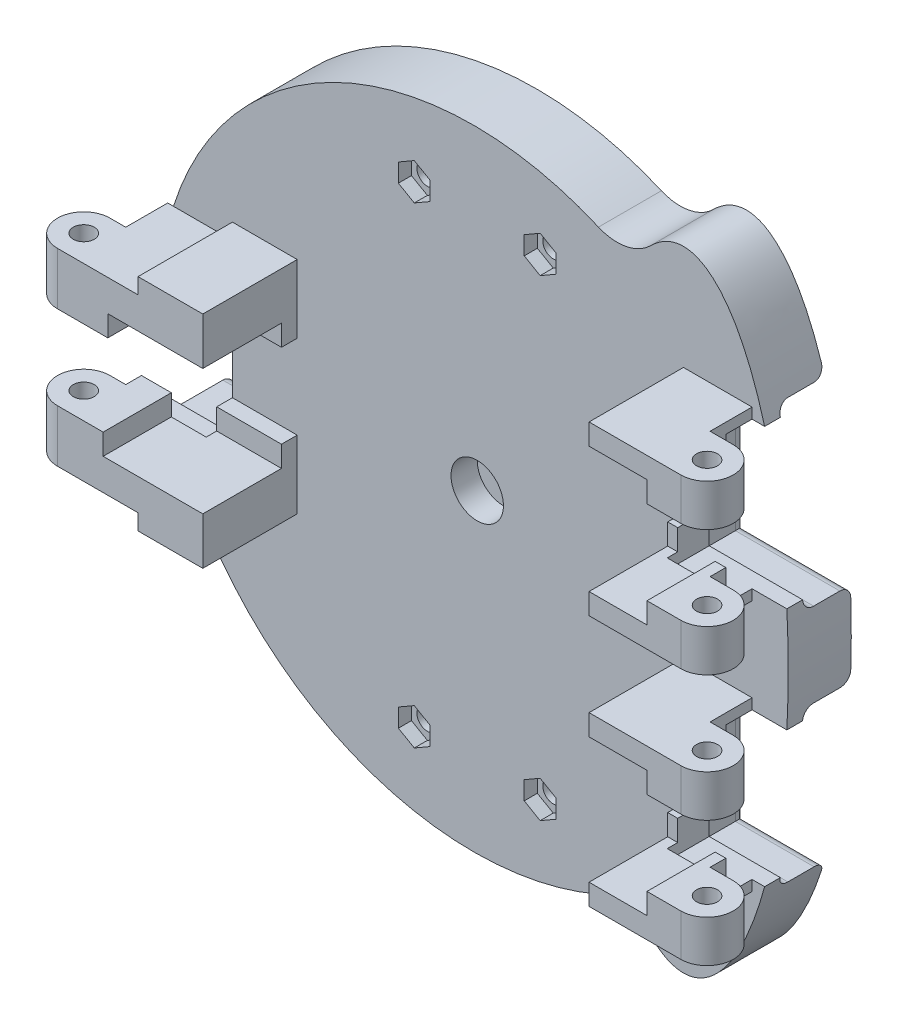
SolidWorks part; units mm, degrees
ref_plane "Front Plane" through (0, 0, 0) normal (1, 0, 0) x (0, 1, 0)
ref_plane "Top Plane" through (0, 0, 0) normal (0, 0, 1) x (0, 1, 0)
ref_plane "Right Plane" through (0, 0, 0) normal (0, 1, 0) x (-1, 0, 0)
sketch "Sketch1" plane through (0, 0, 0) normal (0, 0, 1) x (0, 1, 0)
  line L0 (0, 0) -> (0, 80) construction
  line L1 (0, 0) -> (0, -20) construction
  line L2 (-60, 40) -> (-60, -25.0104) construction
  arc A0 (55.0788, 16.2024) -> (-55.0788, 16.2024) centre (0, 40) ccw
  arc A1 (-56.9566, 6.2888) -> (-55.0788, 16.2024) centre (-63.3406, 12.6327) ccw
  arc A2 (55.0788, 16.2024) -> (56.9566, 6.2888) centre (63.3406, 12.6327) ccw
  ellipse E0 centre (0, 0) end of major axis (60, 0) minor radius 20 (-56.9566, 6.2888) -> (56.9566, 6.2888) ccw
  dimension "D3" = 120
  dimension "D2" = 18
  dimension "D4" = 18
  dimension "D1" = 80
extrude "Boss-Extrude1" add sketch "Sketch1" along normal blind 12
sketch "Sketch3" plane through (0, 0, 12) normal (0, 0, 1) x (1, 0, 0)
  line L0 (20, 0) -> (-100, 0) construction
  arc A0 (-16.2024, 55.0788) -> (-16.2024, -55.0788) centre (-40, 0) ccw construction
  circle A1 centre (-39.3259, 0) radius 5
  ellipse E0 centre (0, 0) end of major axis (0, 60) minor radius 20 (-6.2888, -56.9566) -> (-6.2888, 56.9566) ccw construction
  dimension "D1" = 10
extrude "Cut-Extrude1" cut sketch "Sketch3" against normal blind 5
sketch "Sketch4" plane through (0, 0, 12) normal (0, 0, 1) x (1, 0, 0)
  line L0 (-39.3259, 0) -> (-39.3259, -45) construction
  line L1 (-39.3259, 0) -> (-39.3259, 45) construction
  line L2 (-51.3259, -45) -> (-39.3259, -45) construction
  line L3 (-39.3259, -45) -> (-27.3259, -45) construction
  line L4 (-39.3259, 45) -> (-27.3259, 45) construction
  line L5 (-39.3259, 45) -> (-51.3259, 45) construction
  line L7 (-51.3259, 41.5) -> (-48.2948, 43.25)
  line L8 (-48.2948, 43.25) -> (-48.2948, 46.75)
  line L9 (-48.2948, 46.75) -> (-51.3259, 48.5)
  line L10 (-51.3259, 48.5) -> (-54.357, 46.75)
  line L11 (-54.357, 46.75) -> (-54.357, 43.25)
  line L12 (-54.357, 43.25) -> (-51.3259, 41.5)
  line L13 (-27.3259, 41.5) -> (-24.2948, 43.25)
  line L14 (-24.2948, 43.25) -> (-24.2948, 46.75)
  line L15 (-24.2948, 46.75) -> (-27.3259, 48.5)
  line L16 (-27.3259, 48.5) -> (-30.357, 46.75)
  line L17 (-30.357, 46.75) -> (-30.357, 43.25)
  line L18 (-30.357, 43.25) -> (-27.3259, 41.5)
  line L19 (-51.3259, -48.5) -> (-48.2948, -46.75)
  line L20 (-48.2948, -46.75) -> (-48.2948, -43.25)
  line L21 (-48.2948, -43.25) -> (-51.3259, -41.5)
  line L22 (-51.3259, -41.5) -> (-54.357, -43.25)
  line L23 (-54.357, -43.25) -> (-54.357, -46.75)
  line L24 (-54.357, -46.75) -> (-51.3259, -48.5)
  line L25 (-27.3259, -48.5) -> (-24.2948, -46.75)
  line L26 (-24.2948, -46.75) -> (-24.2948, -43.25)
  line L27 (-24.2948, -43.25) -> (-27.3259, -41.5)
  line L28 (-27.3259, -41.5) -> (-30.357, -43.25)
  line L29 (-30.357, -43.25) -> (-30.357, -46.75)
  line L30 (-30.357, -46.75) -> (-27.3259, -48.5)
  circle A2 centre (-51.3259, 45) radius 3.0311 construction
  circle A3 centre (-27.3259, 45) radius 3.0311 construction
  circle A4 centre (-51.3259, -45) radius 3.0311 construction
  circle A5 centre (-27.3259, -45) radius 3.0311 construction
  dimension "D1" = 45
  dimension "D2" = 45
  dimension "D3" = 12
  dimension "D4" = 12
  dimension "D5" = 12
  dimension "D6" = 12
  dimension "D7" = 7
  dimension "D8" = 7
  dimension "D9" = 7
  dimension "D10" = 7
extrude "Cut-Extrude2" cut sketch "Sketch4" against normal blind 2.5
sketch "Sketch5" plane through (0, 0, 12) normal (0, 0, 1) x (1, 0, 0)
  line L0 (-39.3259, 0) -> (20, 0) construction
  line L1 (-39.3259, 0) -> (-100, 0) construction
  line L2 (-100, 0) -> (-100, 8) construction
  line L3 (-100, 0) -> (-100, -8) construction
  line L4 (-100, 8) -> (-86, 8)
  line L8 (-100, -8) -> (-86, -8)
  line L14 (-105, -8) -> (-100, -8)
  line L15 (-100, 8) -> (-105, 8)
  line L19 (-73.6498, 16) -> (-73.6498, 8)
  line L20 (-73.6498, 8) -> (-86, 8)
  line L21 (-86, -8) -> (-73.6498, -8)
  line L22 (-73.6498, -8) -> (-73.6498, -16)
  line L25 (-86, 17.9882) -> (-86, 21)
  line L27 (-86, 21) -> (-73.6498, 21)
  line L28 (-73.6498, 21) -> (-73.6498, 16)
  line L29 (-86, -17.9929) -> (-86, -21)
  line L30 (-86, -21) -> (-73.6498, -21)
  line L31 (-73.6498, -21) -> (-73.6498, -16)
  line L36 (-86, -17.9929) -> (-117, -17.9929)
  line L37 (-86, 17.9882) -> (-117, 17.9882)
  line L38 (-117, 17.9882) -> (-117, 8)
  line L39 (-117, 8) -> (-105, 8)
  line L40 (-117, -17.9929) -> (-117, -8)
  line L41 (-117, -8) -> (-105, -8)
  arc A0 (-16.2024, 55.0788) -> (-16.2024, -55.0788) centre (-40, 0) ccw construction
  ellipse E0 centre (0, 0) end of major axis (0, 60) minor radius 20 (-6.2888, -56.9566) -> (-6.2888, 56.9566) ccw construction
  dimension "D1" = 8
  dimension "D2" = 8
  dimension "D3" = 31
extrude "Boss-Extrude2" add sketch "Sketch5" along normal blind 18
sketch "Sketch6" plane through (0, 0, 12) normal (0, 0, 1) x (1, 0, 0)
  line L0 (0, 0) -> (-39.3259, 0) construction
  line L1 (0, 0) -> (20, 0) construction
  line L2 (20, 0) -> (20, 8) construction
  line L3 (20, 0) -> (20, -8) construction
  line L4 (20, 8) -> (-39.3259, 8) construction
  line L5 (-39.3259, 8) -> (-39.3259, 0) construction
  line L6 (-39.3259, 0) -> (-39.3259, -8) construction
  line L7 (-39.3259, -8) -> (20, -8) construction
  line L8 (20, 8) -> (20, 16) construction
  line L9 (20, 16) -> (20, 32) construction
  line L10 (20, 32) -> (20, 40) construction
  line L11 (20, -8) -> (20, -16) construction
  line L12 (20, -16) -> (20, -32) construction
  line L13 (20, -32) -> (20, -40) construction
  line L15 (20, 40) -> (0, 40)
  line L16 (0, 40) -> (0, 32)
  line L17 (0, 32) -> (20, 32)
  line L18 (20, 8) -> (0, 8)
  line L19 (0, 8) -> (0, 16)
  line L20 (0, 16) -> (20, 16)
  line L23 (20, -16) -> (0, -16)
  line L24 (0, -16) -> (0, -8)
  line L25 (0, -8) -> (20, -8)
  line L27 (20, -40) -> (0, -40)
  line L28 (0, -40) -> (0, -32)
  line L29 (0, -32) -> (18.7036, -32)
  line L30 (20, 40) -> (30, 40)
  line L31 (30, 40) -> (30, 32)
  line L32 (30, 32) -> (20, 32)
  line L33 (20, 16) -> (30, 16)
  line L34 (30, 16) -> (30, 8)
  line L35 (30, 8) -> (20, 8)
  line L36 (20, -8) -> (30, -8)
  line L37 (30, -8) -> (30, -16)
  line L38 (30, -16) -> (20, -16)
  line L42 (18.7036, -32) -> (30, -32)
  line L43 (30, -32) -> (30, -40)
  line L44 (30, -40) -> (20, -40)
  ellipse E0 centre (0, 0) end of major axis (0, 60) minor radius 20 (-6.2888, -56.9566) -> (-6.2888, 56.9566) ccw construction
  dimension "D1" = 8
  dimension "D2" = 8
  dimension "D3" = 8
  dimension "D4" = 16
  dimension "D5" = 8
  dimension "D6" = 8
  dimension "D7" = 16
  dimension "D8" = 8
  dimension "D9" = 10
extrude "Boss-Extrude3" add sketch "Sketch6" along normal blind 18
sketch "Sketch11" plane through (0, 0, 12) normal (0, 0, 1) x (1, 0, 0)
  line L0 (-51.3259, 48.5) -> (-51.3259, 41.5) construction
  line L1 (-51.3259, 41.5) -> (-51.3259, -41.5) construction
  line L2 (-51.3259, -41.5) -> (-51.3259, -48.5) construction
  line L3 (-51.3259, -48.5) -> (-27.3259, -48.5) construction
  line L4 (-27.3259, -48.5) -> (-27.3259, -41.5) construction
  line L5 (-27.3259, -41.5) -> (-27.3259, 41.5) construction
  line L6 (-27.3259, 41.5) -> (-27.3259, 48.5) construction
  line L7 (-27.3259, 48.5) -> (-51.3259, 48.5) construction
  circle A0 centre (-51.3259, 45) radius 2
  circle A1 centre (-51.3259, -45) radius 2
  circle A2 centre (-27.3259, -45) radius 2
  circle A3 centre (-27.3259, 45) radius 2
  dimension "D1" = 4
  dimension "D2" = 4
  dimension "D3" = 4
  dimension "D4" = 4
extrude "Cut-Extrude5" cut sketch "Sketch11" against normal blind 20
sketch "Sketch14" plane through (0, 0, 0) normal (0, 0, -1) x (1, 0, 0)
  line L0 (-100, 0) -> (-86, 0) construction
  line L1 (20, 0) -> (0, 0) construction
  line L2 (-86, 0) -> (-86, 14)
  line L3 (-86, 0) -> (-86, -14)
  line L6 (-86, 14) -> (-86, 16)
  line L7 (-97.8273, 16) -> (-86, 16)
  line L8 (-97.8273, -16) -> (-86, -16)
  line L9 (-86, -16) -> (-86, -14)
  arc A0 (-16.2024, 55.0788) -> (-16.2024, -55.0788) centre (-40, 0) ccw construction
  arc A2 (-97.8273, 16) -> (-97.8273, -16) centre (-40, 0) ccw
  ellipse E0 centre (0, 0) end of major axis (0, -60) minor radius 20 (-6.2888, -56.9566) -> (-6.2888, 56.9566) ccw construction
  dimension "D1" = 14
  dimension "D2" = 14
  dimension "D3" = 14
extrude "Cut-Extrude13" cut sketch "Sketch14" against normal blind 12
sketch "Sketch16" plane through (0, -40, 0) normal (0, -1, 0) x (1, 0, 0)
  line L2 (17.5, 25) -> (17.5, 12) construction
  line L3 (14.9071, 12) -> (30, 12) construction
  circle A0 centre (17.5, 25) radius 2
  dimension "D2" = 4
  dimension "D1" = 13
extrude "Cut-Extrude14" cut sketch "Sketch16" against normal blind 90
sketch "Sketch17" plane through (0, -40, 0) normal (0, -1, 0) x (1, 0, 0)
  line L0 (17.5, 30) -> (30, 30)
  line L1 (30, 30) -> (30, 20)
  line L2 (30, 30) -> (30, 12) construction
  line L3 (30, 20) -> (17.5, 20)
  arc A0 (17.5, 20) -> (17.5, 30) centre (17.5, 25) ccw
extrude "Cut-Extrude15" cut sketch "Sketch17" against normal blind 81
sketch "Sketch20" plane through (0, 0, 0) normal (0, 0, -1) x (1, 0, 0)
  line L0 (22.5, 32) -> (-0.0929, 32) construction
  line L1 (-0.0929, 32) -> (-0.0929, -33.9584) construction
  line L2 (16.9181, -32) -> (-0.0929, -32) construction
  line L3 (22.5, -16) -> (-0.0929, -16) construction
  line L4 (23.5, 16) -> (-0.0929, 16) construction
  line L5 (22.5, 16) -> (17.5, 16) construction
  line L6 (23.5, 40) -> (-0.0929, 40) construction
  line L7 (22.5, 40) -> (17.5, 40) construction
  line L8 (-0.0929, 40) -> (-0.0929, 32) construction
  line L9 (22.5, -40) -> (-0.0929, -40) construction
  line L10 (-0.0929, -40) -> (-0.0929, -33.9584) construction
  line L11 (14.9071, 40) -> (-0.0929, 40)
  line L13 (19.8214, 8) -> (-0.0929, 8)
  line L14 (-0.0929, 8) -> (-0.0929, 40)
  line L17 (14.9071, -40) -> (-0.0929, -40)
  line L18 (-0.0929, -40) -> (-0.0929, -8)
  line L19 (-0.0929, -8) -> (19.8214, -8)
  ellipse E0 centre (0, 0) end of major axis (0, 60) minor radius 20 (14.9071, -40) -> (19.8214, -8) ccw
  ellipse E1 centre (0, 0) end of major axis (0, -60) minor radius 20 (-6.2888, -56.9566) -> (-6.2888, 56.9566) ccw construction
  ellipse E2 centre (0, 0) end of major axis (0, 60) minor radius 20 (19.8214, 8) -> (14.9071, 40) ccw
  dimension "D1" = 15
extrude "Cut-Extrude19" cut sketch "Sketch20" against normal blind 9
sketch "Sketch21" plane through (0, 0, 9) normal (0, 0, -1) x (1, 0, 0)
  line L0 (16.6029, 33.4528) -> (3.2905, 33.4528)
  line L2 (3.2905, 33.4528) -> (3.2905, 14.0721)
  line L3 (3.2905, 14.0721) -> (19.4422, 14.0721)
  line L6 (19.4285, -14.2406) -> (3.2905, -14.2406)
  line L8 (3.2905, -14.2406) -> (3.2905, -34.1269)
  line L9 (3.2905, -34.1269) -> (16.4498, -34.1269)
  ellipse E0 centre (0, 0) end of major axis (0, 60) minor radius 20 (16.4498, -34.1269) -> (19.4285, -14.2406) ccw
  ellipse E1 centre (0, 0) end of major axis (0, -60) minor radius 20 (19.8214, -8) -> (19.8214, 8) ccw construction
  ellipse E2 centre (0, 0) end of major axis (0, 60) minor radius 20 (19.4422, 14.0721) -> (16.6029, 33.4528) ccw
extrude "Cut-Extrude22" cut sketch "Sketch21" against normal blind 3
sketch "Sketch22" plane through (0, 0, 30) normal (0, 0, 1) x (1, 0, 0)
  line L0 (-73.6498, 12) -> (-91.7593, 12)
  line L1 (-73.6498, 8) -> (-73.6498, 21) construction
  line L2 (-91.7593, 12) -> (-91.7593, 8)
  line L3 (-117, 8) -> (-73.6498, 8) construction
  line L4 (-91.7593, 8) -> (-73.6498, 8)
  line L5 (-73.6498, 8) -> (-73.6498, 12)
  line L6 (-73.6498, -8) -> (-92.6498, -8)
  line L7 (-92.6498, -8) -> (-92.6498, -12)
  line L8 (-92.6498, -12) -> (-73.6498, -12)
  line L9 (-73.6498, -12) -> (-73.6498, -8)
  line L10 (0, 32) -> (0, 36)
  line L11 (0, 40) -> (0, 32) construction
  line L12 (0, 36) -> (11.0428, 36)
  line L13 (11.0428, 36) -> (11.0428, 32)
  line L14 (0, 32) -> (17.5, 32) construction
  line L15 (11.0428, 32) -> (0, 32)
  line L16 (0, 16) -> (11.0428, 16)
  line L17 (17.5, 16) -> (0, 16) construction
  line L18 (11.0428, 16) -> (11.0428, 12)
  line L19 (11.0428, 12) -> (0, 12)
  line L20 (0, 16) -> (0, 8) construction
  line L21 (0, 12) -> (0, 16)
  line L25 (11.0428, -12) -> (0, -12)
  line L26 (0, -8) -> (0, -16) construction
  line L28 (0, -32) -> (11.0428, -32)
  line L29 (17.5, -32) -> (0, -32) construction
  line L30 (11.0428, -32) -> (11.0428, -36)
  line L31 (11.0428, -36) -> (0, -36)
  line L32 (0, -36) -> (0, -32)
  line L33 (0, -16) -> (0, -12)
  line L34 (11.0428, -12) -> (11.0428, -16)
  line L35 (0, -16) -> (17.5, -16) construction
  line L36 (11.0428, -16) -> (0, -16)
  dimension "D1" = 4
  dimension "D2" = 4
  dimension "D3" = 4
  dimension "D4" = 4
  dimension "D5" = 4
  dimension "D6" = 19
extrude "Cut-Extrude23" cut sketch "Sketch22" against normal blind 15
fillet "Fillet3" radius 2 4 edges at (9.9467, -33.4528, 9) (11.3663, -14.0721, 9) (11.3595, 14.2406, 9) (9.8701, 34.1269, 9)
fillet "Fillet4" radius 2 10 edges at (-91.9137, 16, 12) (-91.9137, -16, 12) (15.4511, 38.0967, 9) (7.4071, 40, 9) (-0.0929, 24, 9) (9.8643, 8, 9) (-0.0929, -24, 9) (7.4071, -40, 9) (19.7179, -10.042, 9) (9.8643, -8, 9)
fillet "Fillet5" radius 2 9 edges at (-91.9137, 16, 0) (-86, 0, 0) (-91.9137, -16, 0) (7.4071, -40, 0) (-0.0929, -24, 0) (9.8643, -8, 0) (9.8643, 8, 0) (-0.0929, 24, 0) (7.4071, 40, 0)
sketch "Sketch23" plane through (0, 0, 0) normal (0, 0, -1) x (1, 0, 0)
  line L1 (-27.3259, 49.4) -> (-31.1364, 47.2)
  line L2 (-31.1364, 47.2) -> (-31.1364, 42.8)
  line L3 (-31.1364, 42.8) -> (-27.3259, 40.6)
  line L4 (-27.3259, 40.6) -> (-23.5154, 42.8)
  line L5 (-23.5154, 42.8) -> (-23.5154, 47.2)
  line L6 (-23.5154, 47.2) -> (-27.3259, 49.4)
  line L7 (-51.3259, 49.4) -> (-55.1364, 47.2)
  line L8 (-55.1364, 47.2) -> (-55.1364, 42.8)
  line L9 (-55.1364, 42.8) -> (-51.3259, 40.6)
  line L10 (-51.3259, 40.6) -> (-47.5154, 42.8)
  line L11 (-47.5154, 42.8) -> (-47.5154, 47.2)
  line L12 (-47.5154, 47.2) -> (-51.3259, 49.4)
  line L13 (-27.3259, -49.4) -> (-23.5154, -47.2)
  line L14 (-23.5154, -47.2) -> (-23.5154, -42.8)
  line L15 (-23.5154, -42.8) -> (-27.3259, -40.6)
  line L16 (-27.3259, -40.6) -> (-31.1364, -42.8)
  line L17 (-31.1364, -42.8) -> (-31.1364, -47.2)
  line L18 (-31.1364, -47.2) -> (-27.3259, -49.4)
  line L19 (-51.3259, -49.4) -> (-47.5154, -47.2)
  line L20 (-47.5154, -47.2) -> (-47.5154, -42.8)
  line L21 (-47.5154, -42.8) -> (-51.3259, -40.6)
  line L22 (-51.3259, -40.6) -> (-55.1364, -42.8)
  line L23 (-55.1364, -42.8) -> (-55.1364, -47.2)
  line L24 (-55.1364, -47.2) -> (-51.3259, -49.4)
  circle A0 centre (-27.3259, 45) radius 3.8105 construction
  circle A1 centre (-51.3259, 45) radius 3.8105 construction
  circle A2 centre (-27.3259, -45) radius 3.8105 construction
  circle A3 centre (-51.3259, -45) radius 3.8105 construction
  dimension "D1" = 8.8
  dimension "D2" = 8.8
  dimension "D3" = 8.8
  dimension "D4" = 8.8
extrude "Cut-Extrude24" cut sketch "Sketch23" against normal blind 3.5
sketch "Sketch24" plane through (0, 17.9882, 0) normal (0, 1, 0) x (-1, 0, 0)
  line L0 (117, 30) -> (117, 25) construction
  line L1 (117, 25) -> (101.35, 25) construction
  circle A0 centre (101.35, 25) radius 2
  dimension "D3" = 4
  dimension "D1" = 5
  dimension "D2" = 15.65
extrude "Cut-Extrude25" cut sketch "Sketch24" against normal blind 40
sketch "Sketch25" plane through (0, 17.9882, 0) normal (0, 1, 0) x (-1, 0, 0)
  line L0 (98.3438, 12) -> (98.3438, 18.1702)
  line L1 (98.3438, 18.1702) -> (109.6008, 18.1702)
  line L2 (109.6008, 18.1702) -> (109.6008, 30)
  line L3 (86, 30) -> (117, 30) construction
  line L4 (109.6008, 30) -> (117, 30)
  line L5 (117, 30) -> (117, 12)
  line L6 (117, 30) -> (117, 12) construction
  line L7 (97.2401, 12) -> (117, 12) construction
  line L8 (117, 12) -> (98.3438, 12)
extrude "Cut-Extrude26" cut sketch "Sketch25" against normal blind 40
sketch "Sketch27" plane through (0, 40, 0) normal (0, 1, 0) x (-1, 0, 0)
  line L0 (-17.5, 20) -> (-14.9071, 12)
  line L1 (-14.9071, 12) -> (-30, 12)
  line L2 (-30, 12) -> (-30, 20)
  line L3 (-30, 20) -> (-17.5, 20)
extrude "Cut-Extrude27" cut sketch "Sketch27" against normal blind 110
sketch "Sketch28" plane through (0, 40, 0) normal (0, 1, 0) x (-1, 0, 0)
  line L0 (-17.5, 20) -> (-13.0778, 20)
  line L1 (-13.0778, 20) -> (-13.0778, 12)
  line L2 (0, 12) -> (-14.9071, 12) construction
  line L3 (-13.0778, 12) -> (-14.9071, 12)
  line L4 (-14.9071, 12) -> (-17.5, 20)
extrude "Cut-Extrude28" cut sketch "Sketch28" against normal blind 90
sketch "Sketch29" plane through (0, 17.9882, 0) normal (0, 1, 0) x (-1, 0, 0)
  line L1 (98.3438, 18.1702) -> (98.3438, 20)
  line L2 (98.3438, 20) -> (101.35, 20)
  line L3 (101.35, 30) -> (109.6008, 30)
  line L4 (109.6008, 30) -> (109.6008, 18.1702)
  line L5 (109.6008, 18.1702) -> (98.3438, 18.1702)
  arc A0 (101.35, 20) -> (101.35, 30) centre (101.35, 25) ccw
extrude "Cut-Extrude29" cut sketch "Sketch29" against normal blind 40
sketch "Sketch31" plane through (0, 0, 0) normal (0, 0, -1) x (1, 0, 0)
  line L0 (-98.3438, 14) -> (-86, 14)
  line L1 (-86, 14) -> (-86, -14)
  line L3 (-86, -14) -> (-98.3438, -14)
  line L4 (-98.3438, -14) -> (-98.3438, 14)
  line L5 (1.9071, 38) -> (15.4776, 38)
  line L6 (1.9071, -10) -> (1.9071, -38)
  line L7 (1.9071, 10) -> (19.7203, 10)
  line L8 (19.7203, 10) -> (19.7203, 38)
  line L9 (19.7203, 38) -> (15.4776, 38)
  line L10 (1.9071, 38) -> (1.9071, 10)
  line L11 (1.9071, -38) -> (19.7203, -38)
  line L12 (19.7203, -38) -> (19.7203, -10)
  line L13 (19.7203, -10) -> (1.9071, -10)
extrude "Cut-Extrude31" cut sketch "Sketch31" against normal blind 17
